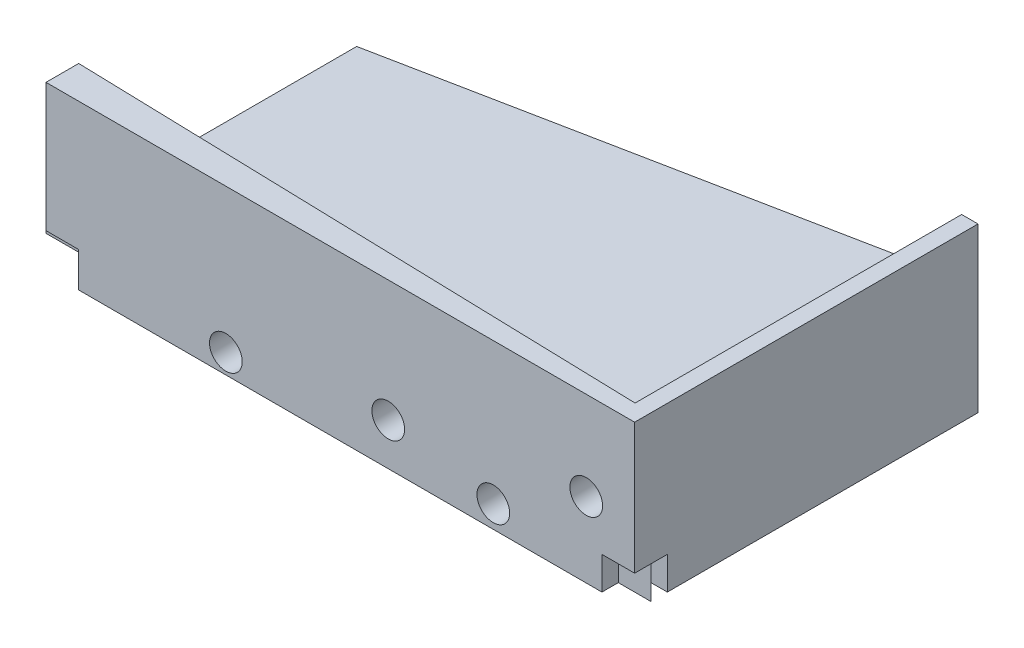
SolidWorks part; units mm, degrees
ref_plane "Plan de face" through (0, 0, 0) normal (0, 0, 1) x (1, 0, 0)
ref_plane "Plan de dessus" through (0, 0, 0) normal (0, 1, 0) x (1, 0, 0)
ref_plane "Plan de droite" through (0, 0, 0) normal (1, 0, 0) x (0, 0, -1)
sketch "Esquisse1" plane through (0, 0, 0) normal (0, 0, 1) x (1, 0, 0)
  line L0 (-105.796, 0) -> (84.204, 0)
  line L1 (84.204, 0) -> (84.204, 33.5021)
  line L2 (84.204, 25.3929) -> (-68.9493, 0) construction
  line L3 (-105.796, 0) -> (-105.796, 2)
  line L4 (-105.796, 2) -> (84.204, 33.5021)
  line L5 (40.9815, 6.7762) -> (8.8615, 12.9011) construction
  line L6 (69.406, 22.9394) -> (40.9815, 6.7762) construction
  circle A0 centre (69.406, 22.9394) radius 3
  circle A1 centre (40.9815, 6.7762) radius 3
  circle A2 centre (-40.796, 6) radius 3
  circle A3 centre (8.8615, 12.9011) radius 3
  dimension "D3" = 6
  dimension "D6" = 6
  dimension "D8" = 6
  dimension "D11" = 6
  dimension "D1" = 190
  dimension "D2" = 2
  dimension "D4" = 15
  dimension "D7" = 8
  dimension "D9" = 6
  dimension "D10" = 65
extrude "Boss.-Extru.1" add sketch "Esquisse1" along normal blind 200
sketch "Esquisse4" plane through (84.204, 0, 0) normal (1, 0, 0) x (0, 0, -1)
  line L1 (-200, 0) -> (-205, 0)
  line L2 (-200, 0) -> (-200, 50)
  line L3 (-200, 50) -> (-205, 50)
  line L4 (-205, 0) -> (-205, 50)
  line L5 (0, 0) -> (5, 0)
  line L6 (0, 0) -> (0, 50)
  line L7 (0, 50) -> (5, 50)
  line L8 (5, 0) -> (5, 50)
  dimension "D1" = 50
  dimension "D2" = 5
  dimension "D3" = 5
  dimension "D4" = 50
extrude "Boss.-Extru.4" add sketch "Esquisse4" against normal blind 180
sketch "Esquisse8" plane through (0, 50, 0) normal (0, 1, 0) x (1, 0, 0)
  line L0 (84.204, 0) -> (-95.796, 0)
  line L1 (-95.796, 0) -> (-95.796, -5)
  line L2 (-95.796, -5) -> (84.204, 0)
  dimension "D1" = 5
extrude "Boss.-Extru.7" add sketch "Esquisse8" against normal up to surface (50 mm away)
ref_plane "Plan2" through (-5.796, 0, 0) normal (1, 0, 0) x (0, 0, -1)
sketch "Esquisse6" plane through (0, 0, -5) normal (0, 0, -1) x (-1, 0, 0)
  line L1 (105.796, 0) -> (85.796, 0)
  line L2 (105.796, 0) -> (105.796, 10.7198)
  line L3 (105.796, 10.7198) -> (85.796, 10.7198)
  line L4 (85.796, 0) -> (85.796, 10.7198)
  line L5 (95.796, 0) -> (95.796, 50) construction
  dimension "D1" = 10
extrude "Enlèv. mat.-Extru.2" cut sketch "Esquisse6" against normal blind 10
ref_plane "Plan3" through (0, 0, 100) normal (0, 0, -1) x (-1, 0, 0)
sketch "Esquisse5" plane through (84.204, 0, 0) normal (1, 0, 0) x (0, 0, -1)
  line L1 (-205, 0) -> (-195, 0)
  line L2 (-205, 0) -> (-205, 10)
  line L3 (-205, 10) -> (-195, 10)
  line L4 (-195, 0) -> (-195, 10)
  line L5 (5, 0) -> (-5, 0)
  line L6 (5, 0) -> (5, 10)
  line L7 (5, 10) -> (-5, 10)
  line L8 (-5, 0) -> (-5, 10)
  dimension "D1" = 10
  dimension "D2" = 10
  dimension "D3" = 10
  dimension "D4" = 10
extrude "Enlèv. mat.-Extru.1" cut sketch "Esquisse5" against normal blind 10
sketch "Esquisse14" plane through (0, 0, -5) normal (0, 0, -1) x (-1, 0, 0)
  circle A0 centre (-69.406, 22.9394) radius 5
  circle A1 centre (-40.9815, 6.7762) radius 5
  circle A2 centre (-8.8615, 12.9011) radius 5
  circle A3 centre (40.796, 6) radius 5
  dimension "D1" = 10
  dimension "D2" = 10
  dimension "D3" = 10
  dimension "D4" = 10
extrude "Enlèv. mat.-Extru.4" cut sketch "Esquisse14" against normal blind 15
mirror "Symétrie3" about plane through (0, 0, 100) normal (0, 0, -1) of "Enlèv. mat.-Extru.4", "Boss.-Extru.7", "Enlèv. mat.-Extru.2"
sketch "Esquisse15" plane through (0, 0, -5) normal (0, 0, -1) x (-1, 0, 0)
  line L0 (-84.204, 33.5021) -> (-79.204, 32.6731)
  line L1 (-84.204, 33.5021) -> (85.796, 5.316) construction
  line L2 (-79.204, 32.6731) -> (-79.204, 50)
  line L3 (95.796, 50) -> (-84.204, 50) construction
  line L4 (-79.204, 50) -> (-84.204, 50)
  line L5 (-84.204, 50) -> (-84.204, 33.5021)
  dimension "D1" = 5
extrude "Boss.-Extru.8" add sketch "Esquisse15" against normal up to surface (204.8611 mm away)
sketch "Esquisse16" plane through (0, 0, 100) normal (0, 0, -1) x (-1, 0, 0)
  line L0 (5.796, 27.5) -> (5.796, -27.5) construction
  line L1 (111.2335, 66.5717) -> (-99.6415, 66.5717)
  line L2 (111.2335, 66.5717) -> (111.2335, -16.17)
  line L3 (111.2335, -16.17) -> (-99.6415, -16.17)
  line L4 (-99.6415, 66.5717) -> (-99.6415, -16.17)
  line L5 (111.2335, 66.5717) -> (-99.6415, -16.17) construction
  line L6 (111.2335, -16.17) -> (-99.6415, 66.5717) construction
  point P0 (5.796, 25.2008)
extrude "Enlèv. mat.-Extru.5" cut sketch "Esquisse16" along normal blind 130
